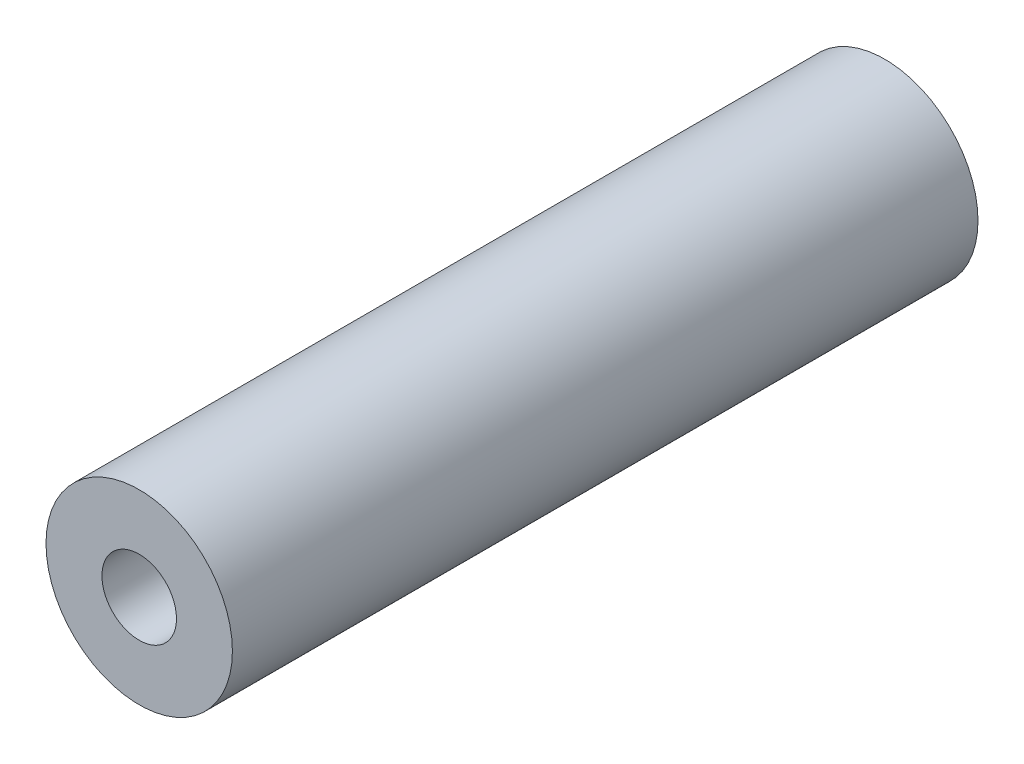
SolidWorks part; units mm, degrees
material "SKD11淬火HRC56-60"
ref_plane "前基準面" through (0, 0, 0) normal (0, 0, 1) x (1, 0, 0)
ref_plane "上基準面" through (0, 0, 0) normal (0, 1, 0) x (1, 0, 0)
ref_plane "右基準面" through (0, 0, 0) normal (1, 0, 0) x (0, 0, -1)
sketch "草图1" plane through (0, 0, 0) normal (0, 0, 1) x (1, 0, 0)
  circle A0 centre (0, 0) radius 2.5
  circle A1 centre (0, 0) radius 1
  dimension "D1" = 2
  dimension "D2" = 5
extrude "凸台-拉伸1" add sketch "草图1" along normal blind 20
